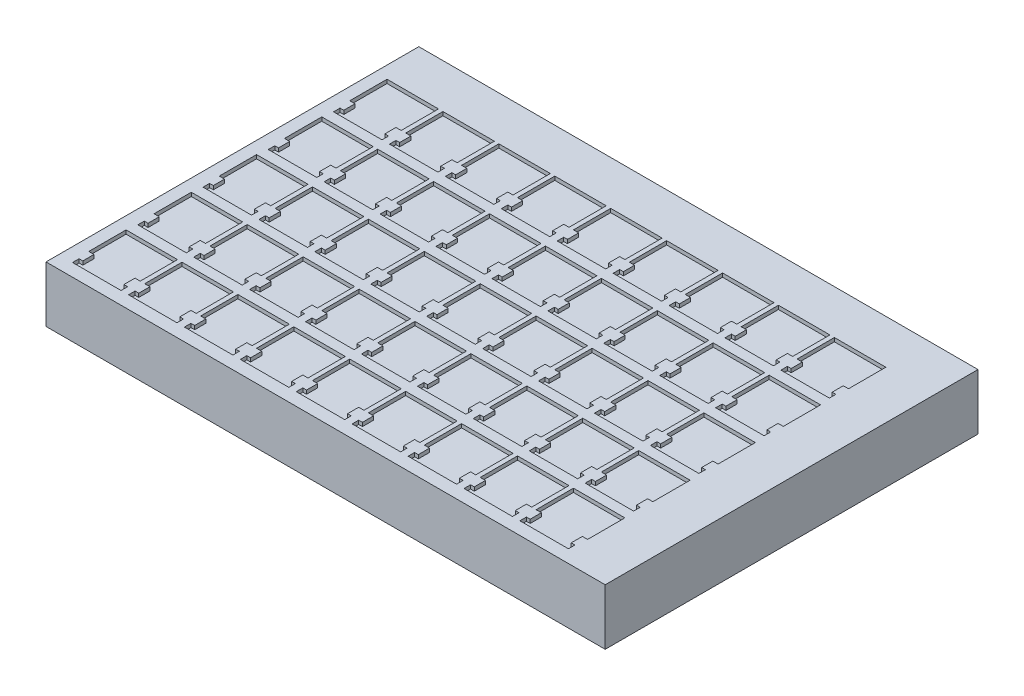
SolidWorks part; units mm, degrees
ref_plane "Front Plane" through (0, 0, 0) normal (0, 0, 1) x (1, 0, 0)
ref_plane "Top Plane" through (0, 0, 0) normal (0, 1, 0) x (1, 0, 0)
ref_plane "Right Plane" through (0, 0, 0) normal (1, 0, 0) x (0, 0, -1)
sketch "Sketch1" plane through (0, 0, 0) normal (0, 1, 0) x (1, 0, 0)
  line L1 (0, 0) -> (300, 0)
  line L2 (0, 0) -> (0, 200)
  line L3 (0, 200) -> (300, 200)
  line L4 (300, 0) -> (300, 200)
  dimension "D1" = 300
  dimension "D2" = 200
extrude "Boss-Extrude1" add sketch "Sketch1" along normal blind 30
sketch "Sketch2" plane through (0, 30, 0) normal (0, 1, 0) x (1, 0, 0)
  line L0 (8.4047, 7.8512) -> (8.4047, 9.3512) construction
  line L1 (8.4047, 9.3512) -> (10.4047, 9.3512) construction
  line L2 (10.4047, 9.3512) -> (10.4047, 17.3512) construction
  line L3 (10.4047, 17.3512) -> (7.6047, 17.3512) construction
  line L4 (7.6047, 17.3512) -> (7.6047, 35.3512) construction
  line L5 (7.6047, 35.3512) -> (33.2047, 35.3512) construction
  line L6 (33.2047, 35.3512) -> (33.2047, 17.3512) construction
  line L7 (33.2047, 17.3512) -> (30.4047, 17.3512) construction
  line L8 (30.4047, 17.3512) -> (30.4047, 9.3512) construction
  line L9 (30.4047, 9.3512) -> (32.4047, 9.3512) construction
  line L10 (32.4047, 9.3512) -> (32.4047, 7.8512) construction
  line L11 (32.4047, 7.8512) -> (8.4047, 7.8512) construction
  line L12 (33.4047, 6.8512) -> (7.4047, 6.8512)
  line L13 (7.4047, 6.8512) -> (7.4047, 10.3512)
  line L14 (7.4047, 10.3512) -> (9.4047, 10.3512)
  line L15 (9.4047, 10.3512) -> (9.4047, 16.3512)
  line L16 (9.4047, 16.3512) -> (6.6047, 16.3512)
  line L17 (6.6047, 16.3512) -> (6.6047, 36.3512)
  line L18 (6.6047, 36.3512) -> (34.2047, 36.3512)
  line L19 (34.2047, 36.3512) -> (34.2047, 16.3512)
  line L20 (34.2047, 16.3512) -> (31.4047, 16.3512)
  line L21 (31.4047, 16.3512) -> (31.4047, 10.3512)
  line L22 (31.4047, 10.3512) -> (33.4047, 10.3512)
  line L23 (33.4047, 10.3512) -> (33.4047, 6.8512)
  line L24 (63.4047, 6.8512) -> (37.4047, 6.8512)
  line L25 (37.4047, 6.8512) -> (37.4047, 10.3512)
  line L26 (37.4047, 10.3512) -> (39.4047, 10.3512)
  line L27 (39.4047, 10.3512) -> (39.4047, 16.3512)
  line L28 (39.4047, 16.3512) -> (36.6047, 16.3512)
  line L29 (36.6047, 16.3512) -> (36.6047, 36.3512)
  line L30 (36.6047, 36.3512) -> (64.2047, 36.3512)
  line L31 (64.2047, 36.3512) -> (64.2047, 16.3512)
  line L32 (64.2047, 16.3512) -> (61.4047, 16.3512)
  line L33 (61.4047, 16.3512) -> (61.4047, 10.3512)
  line L34 (61.4047, 10.3512) -> (63.4047, 10.3512)
  line L35 (63.4047, 10.3512) -> (63.4047, 6.8512)
  line L36 (93.4047, 6.8512) -> (67.4047, 6.8512)
  line L37 (67.4047, 6.8512) -> (67.4047, 10.3512)
  line L38 (67.4047, 10.3512) -> (69.4047, 10.3512)
  line L39 (69.4047, 10.3512) -> (69.4047, 16.3512)
  line L40 (69.4047, 16.3512) -> (66.6047, 16.3512)
  line L41 (66.6047, 16.3512) -> (66.6047, 36.3512)
  line L42 (66.6047, 36.3512) -> (94.2047, 36.3512)
  line L43 (94.2047, 36.3512) -> (94.2047, 16.3512)
  line L44 (94.2047, 16.3512) -> (91.4047, 16.3512)
  line L45 (91.4047, 16.3512) -> (91.4047, 10.3512)
  line L46 (91.4047, 10.3512) -> (93.4047, 10.3512)
  line L47 (93.4047, 10.3512) -> (93.4047, 6.8512)
  line L48 (123.4047, 6.8512) -> (97.4047, 6.8512)
  line L49 (97.4047, 6.8512) -> (97.4047, 10.3512)
  line L50 (97.4047, 10.3512) -> (99.4047, 10.3512)
  line L51 (99.4047, 10.3512) -> (99.4047, 16.3512)
  line L52 (99.4047, 16.3512) -> (96.6047, 16.3512)
  line L53 (96.6047, 16.3512) -> (96.6047, 36.3512)
  line L54 (96.6047, 36.3512) -> (124.2047, 36.3512)
  line L55 (124.2047, 36.3512) -> (124.2047, 16.3512)
  line L56 (124.2047, 16.3512) -> (121.4047, 16.3512)
  line L57 (121.4047, 16.3512) -> (121.4047, 10.3512)
  line L58 (121.4047, 10.3512) -> (123.4047, 10.3512)
  line L59 (123.4047, 10.3512) -> (123.4047, 6.8512)
  line L60 (153.4047, 6.8512) -> (127.4047, 6.8512)
  line L61 (127.4047, 6.8512) -> (127.4047, 10.3512)
  line L62 (127.4047, 10.3512) -> (129.4047, 10.3512)
  line L63 (129.4047, 10.3512) -> (129.4047, 16.3512)
  line L64 (129.4047, 16.3512) -> (126.6047, 16.3512)
  line L65 (126.6047, 16.3512) -> (126.6047, 36.3512)
  line L66 (126.6047, 36.3512) -> (154.2047, 36.3512)
  line L67 (154.2047, 36.3512) -> (154.2047, 16.3512)
  line L68 (154.2047, 16.3512) -> (151.4047, 16.3512)
  line L69 (151.4047, 16.3512) -> (151.4047, 10.3512)
  line L70 (151.4047, 10.3512) -> (153.4047, 10.3512)
  line L71 (153.4047, 10.3512) -> (153.4047, 6.8512)
  line L72 (183.4047, 6.8512) -> (157.4047, 6.8512)
  line L73 (157.4047, 6.8512) -> (157.4047, 10.3512)
  line L74 (157.4047, 10.3512) -> (159.4047, 10.3512)
  line L75 (159.4047, 10.3512) -> (159.4047, 16.3512)
  line L76 (159.4047, 16.3512) -> (156.6047, 16.3512)
  line L77 (156.6047, 16.3512) -> (156.6047, 36.3512)
  line L78 (156.6047, 36.3512) -> (184.2047, 36.3512)
  line L79 (184.2047, 36.3512) -> (184.2047, 16.3512)
  line L80 (184.2047, 16.3512) -> (181.4047, 16.3512)
  line L81 (181.4047, 16.3512) -> (181.4047, 10.3512)
  line L82 (181.4047, 10.3512) -> (183.4047, 10.3512)
  line L83 (183.4047, 10.3512) -> (183.4047, 6.8512)
  line L84 (213.4047, 6.8512) -> (187.4047, 6.8512)
  line L85 (187.4047, 6.8512) -> (187.4047, 10.3512)
  line L86 (187.4047, 10.3512) -> (189.4047, 10.3512)
  line L87 (189.4047, 10.3512) -> (189.4047, 16.3512)
  line L88 (189.4047, 16.3512) -> (186.6047, 16.3512)
  line L89 (186.6047, 16.3512) -> (186.6047, 36.3512)
  line L90 (186.6047, 36.3512) -> (214.2047, 36.3512)
  line L91 (214.2047, 36.3512) -> (214.2047, 16.3512)
  line L92 (214.2047, 16.3512) -> (211.4047, 16.3512)
  line L93 (211.4047, 16.3512) -> (211.4047, 10.3512)
  line L94 (211.4047, 10.3512) -> (213.4047, 10.3512)
  line L95 (213.4047, 10.3512) -> (213.4047, 6.8512)
  line L96 (243.4047, 6.8512) -> (217.4047, 6.8512)
  line L97 (217.4047, 6.8512) -> (217.4047, 10.3512)
  line L98 (217.4047, 10.3512) -> (219.4047, 10.3512)
  line L99 (219.4047, 10.3512) -> (219.4047, 16.3512)
  line L100 (219.4047, 16.3512) -> (216.6047, 16.3512)
  line L101 (216.6047, 16.3512) -> (216.6047, 36.3512)
  line L102 (216.6047, 36.3512) -> (244.2047, 36.3512)
  line L103 (244.2047, 36.3512) -> (244.2047, 16.3512)
  line L104 (244.2047, 16.3512) -> (241.4047, 16.3512)
  line L105 (241.4047, 16.3512) -> (241.4047, 10.3512)
  line L106 (241.4047, 10.3512) -> (243.4047, 10.3512)
  line L107 (243.4047, 10.3512) -> (243.4047, 6.8512)
  line L108 (273.4047, 6.8512) -> (247.4047, 6.8512)
  line L109 (247.4047, 6.8512) -> (247.4047, 10.3512)
  line L110 (247.4047, 10.3512) -> (249.4047, 10.3512)
  line L111 (249.4047, 10.3512) -> (249.4047, 16.3512)
  line L112 (249.4047, 16.3512) -> (246.6047, 16.3512)
  line L113 (246.6047, 16.3512) -> (246.6047, 36.3512)
  line L114 (246.6047, 36.3512) -> (274.2047, 36.3512)
  line L115 (274.2047, 36.3512) -> (274.2047, 16.3512)
  line L116 (274.2047, 16.3512) -> (271.4047, 16.3512)
  line L117 (271.4047, 16.3512) -> (271.4047, 10.3512)
  line L118 (271.4047, 10.3512) -> (273.4047, 10.3512)
  line L119 (273.4047, 10.3512) -> (273.4047, 6.8512)
  line L120 (63.4047, 41.8512) -> (37.4047, 41.8512)
  line L121 (37.4047, 41.8512) -> (37.4047, 45.3512)
  line L122 (37.4047, 45.3512) -> (39.4047, 45.3512)
  line L123 (39.4047, 45.3512) -> (39.4047, 51.3512)
  line L124 (39.4047, 51.3512) -> (36.6047, 51.3512)
  line L125 (36.6047, 51.3512) -> (36.6047, 71.3512)
  line L126 (36.6047, 71.3512) -> (64.2047, 71.3512)
  line L127 (64.2047, 71.3512) -> (64.2047, 51.3512)
  line L128 (64.2047, 51.3512) -> (61.4047, 51.3512)
  line L129 (61.4047, 51.3512) -> (61.4047, 45.3512)
  line L130 (61.4047, 45.3512) -> (63.4047, 45.3512)
  line L131 (63.4047, 45.3512) -> (63.4047, 41.8512)
  line L132 (93.4047, 41.8512) -> (67.4047, 41.8512)
  line L133 (67.4047, 41.8512) -> (67.4047, 45.3512)
  line L134 (67.4047, 45.3512) -> (69.4047, 45.3512)
  line L135 (69.4047, 45.3512) -> (69.4047, 51.3512)
  line L136 (69.4047, 51.3512) -> (66.6047, 51.3512)
  line L137 (66.6047, 51.3512) -> (66.6047, 71.3512)
  line L138 (66.6047, 71.3512) -> (94.2047, 71.3512)
  line L139 (94.2047, 71.3512) -> (94.2047, 51.3512)
  line L140 (94.2047, 51.3512) -> (91.4047, 51.3512)
  line L141 (91.4047, 51.3512) -> (91.4047, 45.3512)
  line L142 (91.4047, 45.3512) -> (93.4047, 45.3512)
  line L143 (93.4047, 45.3512) -> (93.4047, 41.8512)
  line L144 (123.4047, 41.8512) -> (97.4047, 41.8512)
  line L145 (97.4047, 41.8512) -> (97.4047, 45.3512)
  line L146 (97.4047, 45.3512) -> (99.4047, 45.3512)
  line L147 (99.4047, 45.3512) -> (99.4047, 51.3512)
  line L148 (99.4047, 51.3512) -> (96.6047, 51.3512)
  line L149 (96.6047, 51.3512) -> (96.6047, 71.3512)
  line L150 (96.6047, 71.3512) -> (124.2047, 71.3512)
  line L151 (124.2047, 71.3512) -> (124.2047, 51.3512)
  line L152 (124.2047, 51.3512) -> (121.4047, 51.3512)
  line L153 (121.4047, 51.3512) -> (121.4047, 45.3512)
  line L154 (121.4047, 45.3512) -> (123.4047, 45.3512)
  line L155 (123.4047, 45.3512) -> (123.4047, 41.8512)
  line L156 (153.4047, 41.8512) -> (127.4047, 41.8512)
  line L157 (127.4047, 41.8512) -> (127.4047, 45.3512)
  line L158 (127.4047, 45.3512) -> (129.4047, 45.3512)
  line L159 (129.4047, 45.3512) -> (129.4047, 51.3512)
  line L160 (129.4047, 51.3512) -> (126.6047, 51.3512)
  line L161 (126.6047, 51.3512) -> (126.6047, 71.3512)
  line L162 (126.6047, 71.3512) -> (154.2047, 71.3512)
  line L163 (154.2047, 71.3512) -> (154.2047, 51.3512)
  line L164 (154.2047, 51.3512) -> (151.4047, 51.3512)
  line L165 (151.4047, 51.3512) -> (151.4047, 45.3512)
  line L166 (151.4047, 45.3512) -> (153.4047, 45.3512)
  line L167 (153.4047, 45.3512) -> (153.4047, 41.8512)
  line L168 (183.4047, 41.8512) -> (157.4047, 41.8512)
  line L169 (157.4047, 41.8512) -> (157.4047, 45.3512)
  line L170 (157.4047, 45.3512) -> (159.4047, 45.3512)
  line L171 (159.4047, 45.3512) -> (159.4047, 51.3512)
  line L172 (159.4047, 51.3512) -> (156.6047, 51.3512)
  line L173 (156.6047, 51.3512) -> (156.6047, 71.3512)
  line L174 (156.6047, 71.3512) -> (184.2047, 71.3512)
  line L175 (184.2047, 71.3512) -> (184.2047, 51.3512)
  line L176 (184.2047, 51.3512) -> (181.4047, 51.3512)
  line L177 (181.4047, 51.3512) -> (181.4047, 45.3512)
  line L178 (181.4047, 45.3512) -> (183.4047, 45.3512)
  line L179 (183.4047, 45.3512) -> (183.4047, 41.8512)
  line L180 (213.4047, 41.8512) -> (187.4047, 41.8512)
  line L181 (187.4047, 41.8512) -> (187.4047, 45.3512)
  line L182 (187.4047, 45.3512) -> (189.4047, 45.3512)
  line L183 (189.4047, 45.3512) -> (189.4047, 51.3512)
  line L184 (189.4047, 51.3512) -> (186.6047, 51.3512)
  line L185 (186.6047, 51.3512) -> (186.6047, 71.3512)
  line L186 (186.6047, 71.3512) -> (214.2047, 71.3512)
  line L187 (214.2047, 71.3512) -> (214.2047, 51.3512)
  line L188 (214.2047, 51.3512) -> (211.4047, 51.3512)
  line L189 (211.4047, 51.3512) -> (211.4047, 45.3512)
  line L190 (211.4047, 45.3512) -> (213.4047, 45.3512)
  line L191 (213.4047, 45.3512) -> (213.4047, 41.8512)
  line L192 (243.4047, 41.8512) -> (217.4047, 41.8512)
  line L193 (217.4047, 41.8512) -> (217.4047, 45.3512)
  line L194 (217.4047, 45.3512) -> (219.4047, 45.3512)
  line L195 (219.4047, 45.3512) -> (219.4047, 51.3512)
  line L196 (219.4047, 51.3512) -> (216.6047, 51.3512)
  line L197 (216.6047, 51.3512) -> (216.6047, 71.3512)
  line L198 (216.6047, 71.3512) -> (244.2047, 71.3512)
  line L199 (244.2047, 71.3512) -> (244.2047, 51.3512)
  line L200 (244.2047, 51.3512) -> (241.4047, 51.3512)
  line L201 (241.4047, 51.3512) -> (241.4047, 45.3512)
  line L202 (241.4047, 45.3512) -> (243.4047, 45.3512)
  line L203 (243.4047, 45.3512) -> (243.4047, 41.8512)
  line L204 (273.4047, 41.8512) -> (247.4047, 41.8512)
  line L205 (247.4047, 41.8512) -> (247.4047, 45.3512)
  line L206 (247.4047, 45.3512) -> (249.4047, 45.3512)
  line L207 (249.4047, 45.3512) -> (249.4047, 51.3512)
  line L208 (249.4047, 51.3512) -> (246.6047, 51.3512)
  line L209 (246.6047, 51.3512) -> (246.6047, 71.3512)
  line L210 (246.6047, 71.3512) -> (274.2047, 71.3512)
  line L211 (274.2047, 71.3512) -> (274.2047, 51.3512)
  line L212 (274.2047, 51.3512) -> (271.4047, 51.3512)
  line L213 (271.4047, 51.3512) -> (271.4047, 45.3512)
  line L214 (271.4047, 45.3512) -> (273.4047, 45.3512)
  line L215 (273.4047, 45.3512) -> (273.4047, 41.8512)
  line L216 (63.4047, 76.8512) -> (37.4047, 76.8512)
  line L217 (37.4047, 76.8512) -> (37.4047, 80.3512)
  line L218 (37.4047, 80.3512) -> (39.4047, 80.3512)
  line L219 (39.4047, 80.3512) -> (39.4047, 86.3512)
  line L220 (39.4047, 86.3512) -> (36.6047, 86.3512)
  line L221 (36.6047, 86.3512) -> (36.6047, 106.3512)
  line L222 (36.6047, 106.3512) -> (64.2047, 106.3512)
  line L223 (64.2047, 106.3512) -> (64.2047, 86.3512)
  line L224 (64.2047, 86.3512) -> (61.4047, 86.3512)
  line L225 (61.4047, 86.3512) -> (61.4047, 80.3512)
  line L226 (61.4047, 80.3512) -> (63.4047, 80.3512)
  line L227 (63.4047, 80.3512) -> (63.4047, 76.8512)
  line L228 (93.4047, 76.8512) -> (67.4047, 76.8512)
  line L229 (67.4047, 76.8512) -> (67.4047, 80.3512)
  line L230 (67.4047, 80.3512) -> (69.4047, 80.3512)
  line L231 (69.4047, 80.3512) -> (69.4047, 86.3512)
  line L232 (69.4047, 86.3512) -> (66.6047, 86.3512)
  line L233 (66.6047, 86.3512) -> (66.6047, 106.3512)
  line L234 (66.6047, 106.3512) -> (94.2047, 106.3512)
  line L235 (94.2047, 106.3512) -> (94.2047, 86.3512)
  line L236 (94.2047, 86.3512) -> (91.4047, 86.3512)
  line L237 (91.4047, 86.3512) -> (91.4047, 80.3512)
  line L238 (91.4047, 80.3512) -> (93.4047, 80.3512)
  line L239 (93.4047, 80.3512) -> (93.4047, 76.8512)
  line L240 (123.4047, 76.8512) -> (97.4047, 76.8512)
  line L241 (97.4047, 76.8512) -> (97.4047, 80.3512)
  line L242 (97.4047, 80.3512) -> (99.4047, 80.3512)
  line L243 (99.4047, 80.3512) -> (99.4047, 86.3512)
  line L244 (99.4047, 86.3512) -> (96.6047, 86.3512)
  line L245 (96.6047, 86.3512) -> (96.6047, 106.3512)
  line L246 (96.6047, 106.3512) -> (124.2047, 106.3512)
  line L247 (124.2047, 106.3512) -> (124.2047, 86.3512)
  line L248 (124.2047, 86.3512) -> (121.4047, 86.3512)
  line L249 (121.4047, 86.3512) -> (121.4047, 80.3512)
  line L250 (121.4047, 80.3512) -> (123.4047, 80.3512)
  line L251 (123.4047, 80.3512) -> (123.4047, 76.8512)
  line L252 (153.4047, 76.8512) -> (127.4047, 76.8512)
  line L253 (127.4047, 76.8512) -> (127.4047, 80.3512)
  line L254 (127.4047, 80.3512) -> (129.4047, 80.3512)
  line L255 (129.4047, 80.3512) -> (129.4047, 86.3512)
  line L256 (129.4047, 86.3512) -> (126.6047, 86.3512)
  line L257 (126.6047, 86.3512) -> (126.6047, 106.3512)
  line L258 (126.6047, 106.3512) -> (154.2047, 106.3512)
  line L259 (154.2047, 106.3512) -> (154.2047, 86.3512)
  line L260 (154.2047, 86.3512) -> (151.4047, 86.3512)
  line L261 (151.4047, 86.3512) -> (151.4047, 80.3512)
  line L262 (151.4047, 80.3512) -> (153.4047, 80.3512)
  line L263 (153.4047, 80.3512) -> (153.4047, 76.8512)
  line L264 (183.4047, 76.8512) -> (157.4047, 76.8512)
  line L265 (157.4047, 76.8512) -> (157.4047, 80.3512)
  line L266 (157.4047, 80.3512) -> (159.4047, 80.3512)
  line L267 (159.4047, 80.3512) -> (159.4047, 86.3512)
  line L268 (159.4047, 86.3512) -> (156.6047, 86.3512)
  line L269 (156.6047, 86.3512) -> (156.6047, 106.3512)
  line L270 (156.6047, 106.3512) -> (184.2047, 106.3512)
  line L271 (184.2047, 106.3512) -> (184.2047, 86.3512)
  line L272 (184.2047, 86.3512) -> (181.4047, 86.3512)
  line L273 (181.4047, 86.3512) -> (181.4047, 80.3512)
  line L274 (181.4047, 80.3512) -> (183.4047, 80.3512)
  line L275 (183.4047, 80.3512) -> (183.4047, 76.8512)
  line L276 (213.4047, 76.8512) -> (187.4047, 76.8512)
  line L277 (187.4047, 76.8512) -> (187.4047, 80.3512)
  line L278 (187.4047, 80.3512) -> (189.4047, 80.3512)
  line L279 (189.4047, 80.3512) -> (189.4047, 86.3512)
  line L280 (189.4047, 86.3512) -> (186.6047, 86.3512)
  line L281 (186.6047, 86.3512) -> (186.6047, 106.3512)
  line L282 (186.6047, 106.3512) -> (214.2047, 106.3512)
  line L283 (214.2047, 106.3512) -> (214.2047, 86.3512)
  line L284 (214.2047, 86.3512) -> (211.4047, 86.3512)
  line L285 (211.4047, 86.3512) -> (211.4047, 80.3512)
  line L286 (211.4047, 80.3512) -> (213.4047, 80.3512)
  line L287 (213.4047, 80.3512) -> (213.4047, 76.8512)
  line L288 (243.4047, 76.8512) -> (217.4047, 76.8512)
  line L289 (217.4047, 76.8512) -> (217.4047, 80.3512)
  line L290 (217.4047, 80.3512) -> (219.4047, 80.3512)
  line L291 (219.4047, 80.3512) -> (219.4047, 86.3512)
  line L292 (219.4047, 86.3512) -> (216.6047, 86.3512)
  line L293 (216.6047, 86.3512) -> (216.6047, 106.3512)
  line L294 (216.6047, 106.3512) -> (244.2047, 106.3512)
  line L295 (244.2047, 106.3512) -> (244.2047, 86.3512)
  line L296 (244.2047, 86.3512) -> (241.4047, 86.3512)
  line L297 (241.4047, 86.3512) -> (241.4047, 80.3512)
  line L298 (241.4047, 80.3512) -> (243.4047, 80.3512)
  line L299 (243.4047, 80.3512) -> (243.4047, 76.8512)
  line L300 (273.4047, 76.8512) -> (247.4047, 76.8512)
  line L301 (247.4047, 76.8512) -> (247.4047, 80.3512)
  line L302 (247.4047, 80.3512) -> (249.4047, 80.3512)
  line L303 (249.4047, 80.3512) -> (249.4047, 86.3512)
  line L304 (249.4047, 86.3512) -> (246.6047, 86.3512)
  line L305 (246.6047, 86.3512) -> (246.6047, 106.3512)
  line L306 (246.6047, 106.3512) -> (274.2047, 106.3512)
  line L307 (274.2047, 106.3512) -> (274.2047, 86.3512)
  line L308 (274.2047, 86.3512) -> (271.4047, 86.3512)
  line L309 (271.4047, 86.3512) -> (271.4047, 80.3512)
  line L310 (271.4047, 80.3512) -> (273.4047, 80.3512)
  line L311 (273.4047, 80.3512) -> (273.4047, 76.8512)
  line L312 (63.4047, 111.8512) -> (37.4047, 111.8512)
  line L313 (37.4047, 111.8512) -> (37.4047, 115.3512)
  line L314 (37.4047, 115.3512) -> (39.4047, 115.3512)
  line L315 (39.4047, 115.3512) -> (39.4047, 121.3512)
  line L316 (39.4047, 121.3512) -> (36.6047, 121.3512)
  line L317 (36.6047, 121.3512) -> (36.6047, 141.3512)
  line L318 (36.6047, 141.3512) -> (64.2047, 141.3512)
  line L319 (64.2047, 141.3512) -> (64.2047, 121.3512)
  line L320 (64.2047, 121.3512) -> (61.4047, 121.3512)
  line L321 (61.4047, 121.3512) -> (61.4047, 115.3512)
  line L322 (61.4047, 115.3512) -> (63.4047, 115.3512)
  line L323 (63.4047, 115.3512) -> (63.4047, 111.8512)
  line L324 (93.4047, 111.8512) -> (67.4047, 111.8512)
  line L325 (67.4047, 111.8512) -> (67.4047, 115.3512)
  line L326 (67.4047, 115.3512) -> (69.4047, 115.3512)
  line L327 (69.4047, 115.3512) -> (69.4047, 121.3512)
  line L328 (69.4047, 121.3512) -> (66.6047, 121.3512)
  line L329 (66.6047, 121.3512) -> (66.6047, 141.3512)
  line L330 (66.6047, 141.3512) -> (94.2047, 141.3512)
  line L331 (94.2047, 141.3512) -> (94.2047, 121.3512)
  line L332 (94.2047, 121.3512) -> (91.4047, 121.3512)
  line L333 (91.4047, 121.3512) -> (91.4047, 115.3512)
  line L334 (91.4047, 115.3512) -> (93.4047, 115.3512)
  line L335 (93.4047, 115.3512) -> (93.4047, 111.8512)
  line L336 (123.4047, 111.8512) -> (97.4047, 111.8512)
  line L337 (97.4047, 111.8512) -> (97.4047, 115.3512)
  line L338 (97.4047, 115.3512) -> (99.4047, 115.3512)
  line L339 (99.4047, 115.3512) -> (99.4047, 121.3512)
  line L340 (99.4047, 121.3512) -> (96.6047, 121.3512)
  line L341 (96.6047, 121.3512) -> (96.6047, 141.3512)
  line L342 (96.6047, 141.3512) -> (124.2047, 141.3512)
  line L343 (124.2047, 141.3512) -> (124.2047, 121.3512)
  line L344 (124.2047, 121.3512) -> (121.4047, 121.3512)
  line L345 (121.4047, 121.3512) -> (121.4047, 115.3512)
  line L346 (121.4047, 115.3512) -> (123.4047, 115.3512)
  line L347 (123.4047, 115.3512) -> (123.4047, 111.8512)
  line L348 (153.4047, 111.8512) -> (127.4047, 111.8512)
  line L349 (127.4047, 111.8512) -> (127.4047, 115.3512)
  line L350 (127.4047, 115.3512) -> (129.4047, 115.3512)
  line L351 (129.4047, 115.3512) -> (129.4047, 121.3512)
  line L352 (129.4047, 121.3512) -> (126.6047, 121.3512)
  line L353 (126.6047, 121.3512) -> (126.6047, 141.3512)
  line L354 (126.6047, 141.3512) -> (154.2047, 141.3512)
  line L355 (154.2047, 141.3512) -> (154.2047, 121.3512)
  line L356 (154.2047, 121.3512) -> (151.4047, 121.3512)
  line L357 (151.4047, 121.3512) -> (151.4047, 115.3512)
  line L358 (151.4047, 115.3512) -> (153.4047, 115.3512)
  line L359 (153.4047, 115.3512) -> (153.4047, 111.8512)
  line L360 (183.4047, 111.8512) -> (157.4047, 111.8512)
  line L361 (157.4047, 111.8512) -> (157.4047, 115.3512)
  line L362 (157.4047, 115.3512) -> (159.4047, 115.3512)
  line L363 (159.4047, 115.3512) -> (159.4047, 121.3512)
  line L364 (159.4047, 121.3512) -> (156.6047, 121.3512)
  line L365 (156.6047, 121.3512) -> (156.6047, 141.3512)
  line L366 (156.6047, 141.3512) -> (184.2047, 141.3512)
  line L367 (184.2047, 141.3512) -> (184.2047, 121.3512)
  line L368 (184.2047, 121.3512) -> (181.4047, 121.3512)
  line L369 (181.4047, 121.3512) -> (181.4047, 115.3512)
  line L370 (181.4047, 115.3512) -> (183.4047, 115.3512)
  line L371 (183.4047, 115.3512) -> (183.4047, 111.8512)
  line L372 (213.4047, 111.8512) -> (187.4047, 111.8512)
  line L373 (187.4047, 111.8512) -> (187.4047, 115.3512)
  line L374 (187.4047, 115.3512) -> (189.4047, 115.3512)
  line L375 (189.4047, 115.3512) -> (189.4047, 121.3512)
  line L376 (189.4047, 121.3512) -> (186.6047, 121.3512)
  line L377 (186.6047, 121.3512) -> (186.6047, 141.3512)
  line L378 (186.6047, 141.3512) -> (214.2047, 141.3512)
  line L379 (214.2047, 141.3512) -> (214.2047, 121.3512)
  line L380 (214.2047, 121.3512) -> (211.4047, 121.3512)
  line L381 (211.4047, 121.3512) -> (211.4047, 115.3512)
  line L382 (211.4047, 115.3512) -> (213.4047, 115.3512)
  line L383 (213.4047, 115.3512) -> (213.4047, 111.8512)
  line L384 (243.4047, 111.8512) -> (217.4047, 111.8512)
  line L385 (217.4047, 111.8512) -> (217.4047, 115.3512)
  line L386 (217.4047, 115.3512) -> (219.4047, 115.3512)
  line L387 (219.4047, 115.3512) -> (219.4047, 121.3512)
  line L388 (219.4047, 121.3512) -> (216.6047, 121.3512)
  line L389 (216.6047, 121.3512) -> (216.6047, 141.3512)
  line L390 (216.6047, 141.3512) -> (244.2047, 141.3512)
  line L391 (244.2047, 141.3512) -> (244.2047, 121.3512)
  line L392 (244.2047, 121.3512) -> (241.4047, 121.3512)
  line L393 (241.4047, 121.3512) -> (241.4047, 115.3512)
  line L394 (241.4047, 115.3512) -> (243.4047, 115.3512)
  line L395 (243.4047, 115.3512) -> (243.4047, 111.8512)
  line L396 (273.4047, 111.8512) -> (247.4047, 111.8512)
  line L397 (247.4047, 111.8512) -> (247.4047, 115.3512)
  line L398 (247.4047, 115.3512) -> (249.4047, 115.3512)
  line L399 (249.4047, 115.3512) -> (249.4047, 121.3512)
  line L400 (249.4047, 121.3512) -> (246.6047, 121.3512)
  line L401 (246.6047, 121.3512) -> (246.6047, 141.3512)
  line L402 (246.6047, 141.3512) -> (274.2047, 141.3512)
  line L403 (274.2047, 141.3512) -> (274.2047, 121.3512)
  line L404 (274.2047, 121.3512) -> (271.4047, 121.3512)
  line L405 (271.4047, 121.3512) -> (271.4047, 115.3512)
  line L406 (271.4047, 115.3512) -> (273.4047, 115.3512)
  line L407 (273.4047, 115.3512) -> (273.4047, 111.8512)
  line L408 (63.4047, 146.8512) -> (37.4047, 146.8512)
  line L409 (37.4047, 146.8512) -> (37.4047, 150.3512)
  line L410 (37.4047, 150.3512) -> (39.4047, 150.3512)
  line L411 (39.4047, 150.3512) -> (39.4047, 156.3512)
  line L412 (39.4047, 156.3512) -> (36.6047, 156.3512)
  line L413 (36.6047, 156.3512) -> (36.6047, 176.3512)
  line L414 (36.6047, 176.3512) -> (64.2047, 176.3512)
  line L415 (64.2047, 176.3512) -> (64.2047, 156.3512)
  line L416 (64.2047, 156.3512) -> (61.4047, 156.3512)
  line L417 (61.4047, 156.3512) -> (61.4047, 150.3512)
  line L418 (61.4047, 150.3512) -> (63.4047, 150.3512)
  line L419 (63.4047, 150.3512) -> (63.4047, 146.8512)
  line L420 (93.4047, 146.8512) -> (67.4047, 146.8512)
  line L421 (67.4047, 146.8512) -> (67.4047, 150.3512)
  line L422 (67.4047, 150.3512) -> (69.4047, 150.3512)
  line L423 (69.4047, 150.3512) -> (69.4047, 156.3512)
  line L424 (69.4047, 156.3512) -> (66.6047, 156.3512)
  line L425 (66.6047, 156.3512) -> (66.6047, 176.3512)
  line L426 (66.6047, 176.3512) -> (94.2047, 176.3512)
  line L427 (94.2047, 176.3512) -> (94.2047, 156.3512)
  line L428 (94.2047, 156.3512) -> (91.4047, 156.3512)
  line L429 (91.4047, 156.3512) -> (91.4047, 150.3512)
  line L430 (91.4047, 150.3512) -> (93.4047, 150.3512)
  line L431 (93.4047, 150.3512) -> (93.4047, 146.8512)
  line L432 (123.4047, 146.8512) -> (97.4047, 146.8512)
  line L433 (97.4047, 146.8512) -> (97.4047, 150.3512)
  line L434 (97.4047, 150.3512) -> (99.4047, 150.3512)
  line L435 (99.4047, 150.3512) -> (99.4047, 156.3512)
  line L436 (99.4047, 156.3512) -> (96.6047, 156.3512)
  line L437 (96.6047, 156.3512) -> (96.6047, 176.3512)
  line L438 (96.6047, 176.3512) -> (124.2047, 176.3512)
  line L439 (124.2047, 176.3512) -> (124.2047, 156.3512)
  line L440 (124.2047, 156.3512) -> (121.4047, 156.3512)
  line L441 (121.4047, 156.3512) -> (121.4047, 150.3512)
  line L442 (121.4047, 150.3512) -> (123.4047, 150.3512)
  line L443 (123.4047, 150.3512) -> (123.4047, 146.8512)
  line L444 (153.4047, 146.8512) -> (127.4047, 146.8512)
  line L445 (127.4047, 146.8512) -> (127.4047, 150.3512)
  line L446 (127.4047, 150.3512) -> (129.4047, 150.3512)
  line L447 (129.4047, 150.3512) -> (129.4047, 156.3512)
  line L448 (129.4047, 156.3512) -> (126.6047, 156.3512)
  line L449 (126.6047, 156.3512) -> (126.6047, 176.3512)
  line L450 (126.6047, 176.3512) -> (154.2047, 176.3512)
  line L451 (154.2047, 176.3512) -> (154.2047, 156.3512)
  line L452 (154.2047, 156.3512) -> (151.4047, 156.3512)
  line L453 (151.4047, 156.3512) -> (151.4047, 150.3512)
  line L454 (151.4047, 150.3512) -> (153.4047, 150.3512)
  line L455 (153.4047, 150.3512) -> (153.4047, 146.8512)
  line L456 (183.4047, 146.8512) -> (157.4047, 146.8512)
  line L457 (157.4047, 146.8512) -> (157.4047, 150.3512)
  line L458 (157.4047, 150.3512) -> (159.4047, 150.3512)
  line L459 (159.4047, 150.3512) -> (159.4047, 156.3512)
  line L460 (159.4047, 156.3512) -> (156.6047, 156.3512)
  line L461 (156.6047, 156.3512) -> (156.6047, 176.3512)
  line L462 (156.6047, 176.3512) -> (184.2047, 176.3512)
  line L463 (184.2047, 176.3512) -> (184.2047, 156.3512)
  line L464 (184.2047, 156.3512) -> (181.4047, 156.3512)
  line L465 (181.4047, 156.3512) -> (181.4047, 150.3512)
  line L466 (181.4047, 150.3512) -> (183.4047, 150.3512)
  line L467 (183.4047, 150.3512) -> (183.4047, 146.8512)
  line L468 (213.4047, 146.8512) -> (187.4047, 146.8512)
  line L469 (187.4047, 146.8512) -> (187.4047, 150.3512)
  line L470 (187.4047, 150.3512) -> (189.4047, 150.3512)
  line L471 (189.4047, 150.3512) -> (189.4047, 156.3512)
  line L472 (189.4047, 156.3512) -> (186.6047, 156.3512)
  line L473 (186.6047, 156.3512) -> (186.6047, 176.3512)
  line L474 (186.6047, 176.3512) -> (214.2047, 176.3512)
  line L475 (214.2047, 176.3512) -> (214.2047, 156.3512)
  line L476 (214.2047, 156.3512) -> (211.4047, 156.3512)
  line L477 (211.4047, 156.3512) -> (211.4047, 150.3512)
  line L478 (211.4047, 150.3512) -> (213.4047, 150.3512)
  line L479 (213.4047, 150.3512) -> (213.4047, 146.8512)
  line L480 (243.4047, 146.8512) -> (217.4047, 146.8512)
  line L481 (217.4047, 146.8512) -> (217.4047, 150.3512)
  line L482 (217.4047, 150.3512) -> (219.4047, 150.3512)
  line L483 (219.4047, 150.3512) -> (219.4047, 156.3512)
  line L484 (219.4047, 156.3512) -> (216.6047, 156.3512)
  line L485 (216.6047, 156.3512) -> (216.6047, 176.3512)
  line L486 (216.6047, 176.3512) -> (244.2047, 176.3512)
  line L487 (244.2047, 176.3512) -> (244.2047, 156.3512)
  line L488 (244.2047, 156.3512) -> (241.4047, 156.3512)
  line L489 (241.4047, 156.3512) -> (241.4047, 150.3512)
  line L490 (241.4047, 150.3512) -> (243.4047, 150.3512)
  line L491 (243.4047, 150.3512) -> (243.4047, 146.8512)
  line L492 (273.4047, 146.8512) -> (247.4047, 146.8512)
  line L493 (247.4047, 146.8512) -> (247.4047, 150.3512)
  line L494 (247.4047, 150.3512) -> (249.4047, 150.3512)
  line L495 (249.4047, 150.3512) -> (249.4047, 156.3512)
  line L496 (249.4047, 156.3512) -> (246.6047, 156.3512)
  line L497 (246.6047, 156.3512) -> (246.6047, 176.3512)
  line L498 (246.6047, 176.3512) -> (274.2047, 176.3512)
  line L499 (274.2047, 176.3512) -> (274.2047, 156.3512)
  line L500 (274.2047, 156.3512) -> (271.4047, 156.3512)
  line L501 (271.4047, 156.3512) -> (271.4047, 150.3512)
  line L502 (271.4047, 150.3512) -> (273.4047, 150.3512)
  line L503 (273.4047, 150.3512) -> (273.4047, 146.8512)
  line L504 (33.4047, 41.8512) -> (7.4047, 41.8512)
  line L505 (7.4047, 41.8512) -> (7.4047, 45.3512)
  line L506 (7.4047, 45.3512) -> (9.4047, 45.3512)
  line L507 (9.4047, 45.3512) -> (9.4047, 51.3512)
  line L508 (9.4047, 51.3512) -> (6.6047, 51.3512)
  line L509 (6.6047, 51.3512) -> (6.6047, 71.3512)
  line L510 (6.6047, 71.3512) -> (34.2047, 71.3512)
  line L511 (34.2047, 71.3512) -> (34.2047, 51.3512)
  line L512 (34.2047, 51.3512) -> (31.4047, 51.3512)
  line L513 (31.4047, 51.3512) -> (31.4047, 45.3512)
  line L514 (31.4047, 45.3512) -> (33.4047, 45.3512)
  line L515 (33.4047, 45.3512) -> (33.4047, 41.8512)
  line L516 (33.4047, 76.8512) -> (7.4047, 76.8512)
  line L517 (7.4047, 76.8512) -> (7.4047, 80.3512)
  line L518 (7.4047, 80.3512) -> (9.4047, 80.3512)
  line L519 (9.4047, 80.3512) -> (9.4047, 86.3512)
  line L520 (9.4047, 86.3512) -> (6.6047, 86.3512)
  line L521 (6.6047, 86.3512) -> (6.6047, 106.3512)
  line L522 (6.6047, 106.3512) -> (34.2047, 106.3512)
  line L523 (34.2047, 106.3512) -> (34.2047, 86.3512)
  line L524 (34.2047, 86.3512) -> (31.4047, 86.3512)
  line L525 (31.4047, 86.3512) -> (31.4047, 80.3512)
  line L526 (31.4047, 80.3512) -> (33.4047, 80.3512)
  line L527 (33.4047, 80.3512) -> (33.4047, 76.8512)
  line L528 (33.4047, 111.8512) -> (7.4047, 111.8512)
  line L529 (7.4047, 111.8512) -> (7.4047, 115.3512)
  line L530 (7.4047, 115.3512) -> (9.4047, 115.3512)
  line L531 (9.4047, 115.3512) -> (9.4047, 121.3512)
  line L532 (9.4047, 121.3512) -> (6.6047, 121.3512)
  line L533 (6.6047, 121.3512) -> (6.6047, 141.3512)
  line L534 (6.6047, 141.3512) -> (34.2047, 141.3512)
  line L535 (34.2047, 141.3512) -> (34.2047, 121.3512)
  line L536 (34.2047, 121.3512) -> (31.4047, 121.3512)
  line L537 (31.4047, 121.3512) -> (31.4047, 115.3512)
  line L538 (31.4047, 115.3512) -> (33.4047, 115.3512)
  line L539 (33.4047, 115.3512) -> (33.4047, 111.8512)
  line L540 (33.4047, 146.8512) -> (7.4047, 146.8512)
  line L541 (7.4047, 146.8512) -> (7.4047, 150.3512)
  line L542 (7.4047, 150.3512) -> (9.4047, 150.3512)
  line L543 (9.4047, 150.3512) -> (9.4047, 156.3512)
  line L544 (9.4047, 156.3512) -> (6.6047, 156.3512)
  line L545 (6.6047, 156.3512) -> (6.6047, 176.3512)
  line L546 (6.6047, 176.3512) -> (34.2047, 176.3512)
  line L547 (34.2047, 176.3512) -> (34.2047, 156.3512)
  line L548 (34.2047, 156.3512) -> (31.4047, 156.3512)
  line L549 (31.4047, 156.3512) -> (31.4047, 150.3512)
  line L550 (31.4047, 150.3512) -> (33.4047, 150.3512)
  line L551 (33.4047, 150.3512) -> (33.4047, 146.8512)
  dimension "D2" = 5
  dimension "D1" = 9
extrude "Cut-Extrude1" cut sketch "Sketch2" against normal blind 2
